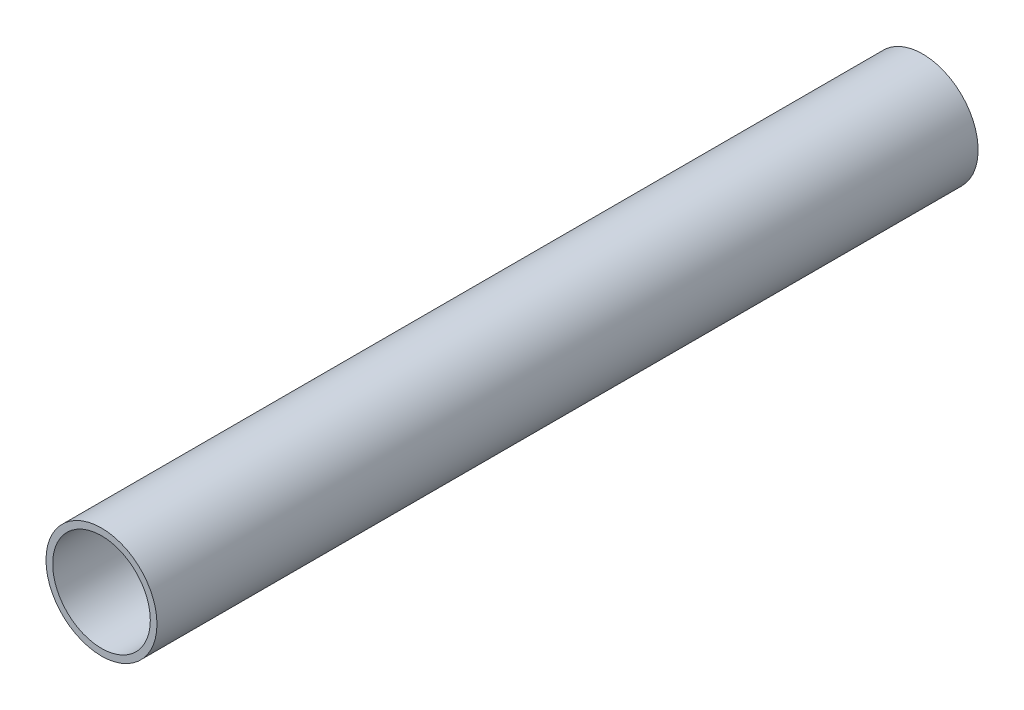
SolidWorks part; units mm, degrees
ref_plane "前视基准面" through (0, 0, 0) normal (0, 0, 1) x (1, 0, 0)
ref_plane "上视基准面" through (0, 0, 0) normal (0, 1, 0) x (1, 0, 0)
ref_plane "右视基准面" through (0, 0, 0) normal (1, 0, 0) x (0, 0, -1)
sketch "草图1" plane through (0, 0, 0) normal (0, 0, 1) x (1, 0, 0)
  circle A0 centre (0, 0) radius 12.5
extrude "凸台-拉伸2" add sketch "草图1" along normal blind 235.43 contours A0
sketch "草图2" plane through (0, 0, 0) normal (0, 0, -1) x (-1, 0, 0)
  circle A0 centre (0, 0) radius 9
extrude "切除-拉伸1" cut sketch "草图2" against normal blind 235.43
sketch "草图3" plane through (0, 0, 0) normal (0, 0, -1) x (-1, 0, 0)
  circle A0 centre (0, 0) radius 12.5
extrude "凸台-拉伸3" add sketch "草图3" along normal blind 15.57
sketch "草图4" plane through (0, 0, -15.57) normal (0, 0, -1) x (-1, 0, 0)
  circle A0 centre (0, 0) radius 9
extrude "切除-拉伸2" cut sketch "草图4" against normal blind 20
sketch "草图5" plane through (0, 0, -15.57) normal (0, 0, -1) x (-1, 0, 0)
  circle A0 centre (0, 0) radius 12.5
extrude "凸台-拉伸4" add sketch "草图5" along normal blind 9.93
sketch "草图6" plane through (0, 0, -25.5) normal (0, 0, -1) x (-1, 0, 0)
  circle A0 centre (0, 0) radius 9
extrude "切除-拉伸3" cut sketch "草图6" against normal blind 10
sketch "草图7" plane through (0, 0, -25.5) normal (0, 0, -1) x (-1, 0, 0)
  circle A0 centre (0, 0) radius 26.8585
extrude "切除-拉伸4" cut sketch "草图7" against normal blind 14.93
sketch "草图8" plane through (0, 0, -10.57) normal (0, 0, -1) x (-1, 0, 0)
  circle A0 centre (0, 0) radius 12.5
extrude "凸台-拉伸5" add sketch "草图8" along normal blind 9.93
sketch "草图9" plane through (0, 0, -20.5) normal (0, 0, -1) x (-1, 0, 0)
  circle A0 centre (0, 0) radius 9
extrude "切除-拉伸5" cut sketch "草图9" against normal blind 10
sketch "草图10" plane through (0, 0, -20.5) normal (0, 0, -1) x (-1, 0, 0)
  circle A0 centre (7.2017, 7.5079) radius 37.1934
extrude "切除-拉伸6" cut sketch "草图10" against normal blind 0.22
sketch "草图11" plane through (0, 0, -20.28) normal (0, 0, -1) x (-1, 0, 0)
  circle A0 centre (-1.2255, 2.3294) radius 43.1872
extrude "切除-拉伸7" cut sketch "草图11" against normal blind 0.71
sketch "草图12" plane through (0, 0, 235.43) normal (0, 0, 1) x (1, 0, 0)
  circle A0 centre (0, 0) radius 12.5
extrude "凸台-拉伸6" add sketch "草图12" along normal blind 15
sketch "草图13" plane through (0, 0, 250.43) normal (0, 0, 1) x (1, 0, 0)
  circle A0 centre (0, 0) radius 9
extrude "切除-拉伸8" cut sketch "草图13" against normal blind 15
sketch "草图14" plane through (0, 0, 250.43) normal (0, 0, 1) x (1, 0, 0)
  circle A0 centre (-6.0646, 3.8171) radius 46.4271
extrude "切除-拉伸9" cut sketch "草图14" against normal blind 85
sketch "草图15" plane through (0, 0, 165.43) normal (0, 0, 1) x (1, 0, 0)
  circle A0 centre (0, 0) radius 11
extrude "切除-拉伸10" cut sketch "草图15" against normal blind 324
